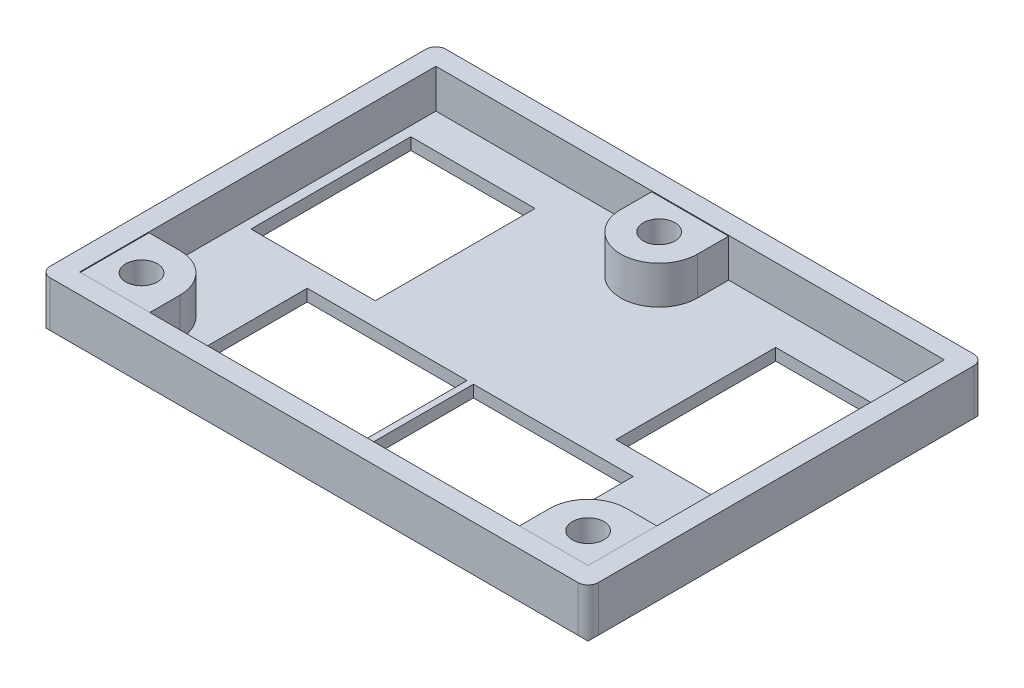
SolidWorks part; units mm, degrees
ref_plane "Front Plane" through (0, 0, 0) normal (0, 0, 1) x (1, 0, 0)
ref_plane "Top Plane" through (0, 0, 0) normal (0, 1, 0) x (1, 0, 0)
ref_plane "Right Plane" through (0, 0, 0) normal (1, 0, 0) x (0, 0, -1)
sketch "Sketch1" plane through (0, 0, 0) normal (0, 1, 0) x (1, 0, 0)
  line L0 (-41.1458, 0) -> (37.3326, 0) construction
  line L1 (-27, -19.5) -> (27, -19.5)
  line L2 (-27, -19.5) -> (-27, 19.5)
  line L3 (-27, 19.5) -> (27, 19.5)
  line L4 (27, -19.5) -> (27, 19.5)
  line L5 (-27, -19.5) -> (27, 19.5) construction
  line L6 (-27, 19.5) -> (27, -19.5) construction
  line L7 (0, 33.589) -> (0, -25.3286) construction
  line L11 (-27, -5) -> (-27, 5)
  point P0 (0, 0)
  point P8 (-32, 0)
  dimension "D1" = 54
  dimension "D2" = 39
extrude "Boss-Extrude1" add sketch "Sketch1" along normal blind 5
sketch "Sketch2" plane through (0, 5, 0) normal (0, 1, 0) x (1, 0, 0)
  line L0 (0, 27.4) -> (0, -30.8783) construction
  line L1 (-42.9811, 0) -> (41.0645, 0) construction
  line L3 (-25.05, -17.55) -> (25.05, -17.55)
  line L4 (-25.05, -17.55) -> (-25.05, 17.55)
  line L5 (-25.05, 17.55) -> (25.05, 17.55)
  line L6 (25.05, -17.55) -> (25.05, 17.55)
  line L7 (-25.05, -17.55) -> (25.05, 17.55) construction
  line L8 (-25.05, 17.55) -> (25.05, -17.55) construction
  point P5 (0, 0)
  dimension "D1" = 50.1
  dimension "D2" = 35.1
extrude "Cut-Extrude1" cut sketch "Sketch2" against normal blind 0.0762
sketch "Sketch3" plane through (0, 4.9238, 0) normal (0, 1, 0) x (1, 0, 0)
  line L0 (0, 25.6254) -> (0, -24.9156) construction
  line L1 (-43.478, 0) -> (41.2775, 0) construction
  line L2 (-5.4043, 14.5) -> (7.1001, 14.5) construction
  line L3 (-3.79, 14.5) -> (-3.79, 17.55)
  line L4 (25.05, 17.55) -> (-25.05, 17.55) construction
  line L5 (3.79, 14.5) -> (3.79, 17.55)
  line L7 (-22, -6.9215) -> (-22, -24.9156) construction
  line L8 (-15.6235, -14.5) -> (-28.7086, -14.5) construction
  line L9 (-18.21, -14.5) -> (-18.21, -17.55)
  line L10 (-25.05, -17.55) -> (25.05, -17.55) construction
  line L11 (-22, -10.71) -> (-25.05, -10.71)
  line L12 (-25.05, 17.55) -> (-25.05, -17.55) construction
  line L13 (-18.21, -17.55) -> (18.21, -17.55)
  line L14 (-25.05, -10.71) -> (-25.05, 17.55)
  line L15 (-25.05, 17.55) -> (-3.79, 17.55)
  line L16 (18.21, -14.5) -> (18.21, -17.55)
  line L17 (22, -10.71) -> (25.05, -10.71)
  line L18 (25.05, -10.71) -> (25.05, 17.55)
  line L19 (25.05, 17.55) -> (3.79, 17.55)
  arc A0 (-3.79, 14.5) -> (3.79, 14.5) centre (0, 14.5) ccw
  arc A1 (-18.21, -14.5) -> (-22, -10.71) centre (-22, -14.5) ccw
  arc A2 (18.21, -14.5) -> (22, -10.71) centre (22, -14.5) cw
  point P31 (0, -17.55)
  dimension "D1" = 7.58
  dimension "D3" = 7.58
  dimension "D2" = 14.5
  dimension "D4" = 22
  dimension "D5" = 14.5
extrude "Cut-Extrude2" cut sketch "Sketch3" against normal blind 3.75
sketch "Sketch4" plane through (0, 4.9238, 0) normal (0, 1, 0) x (1, 0, 0)
  line L0 (0, 26.0262) -> (0, -25.2956) construction
  line L1 (-42.2713, 0) -> (43.691, 0) construction
  circle A0 centre (0, 14.5) radius 1.56
  circle A1 centre (-22, -14.5) radius 1.56
  circle A2 centre (22, -14.5) radius 1.56
  dimension "D1" = 3.12
  dimension "D2" = 14.5
  dimension "D3" = 22
  dimension "D4" = 14.5
extrude "Cut-Extrude3" cut sketch "Sketch4" against normal through all
sketch "Sketch6" plane through (0, 1.1738, 0) normal (0, 1, 0) x (1, 0, 0)
  line L0 (25.05, -17.55) -> (25.05, 17.55) construction
  line L1 (24.1, 14.13) -> (11.85, 14.13)
  line L2 (24.1, 14.13) -> (24.1, -1.62)
  line L3 (24.1, -1.62) -> (11.85, -1.62)
  line L4 (11.85, 14.13) -> (11.85, -1.62)
  line L5 (25.05, 17.55) -> (-25.05, 17.55) construction
  line L6 (-18.21, -17.55) -> (18.21, -17.55) construction
  line L7 (15.85, -3.9) -> (0.1, -3.9)
  line L8 (15.85, -3.9) -> (15.85, -16.4)
  line L9 (15.85, -16.4) -> (0.1, -16.4)
  line L10 (0.1, -3.9) -> (0.1, -16.4)
  line L11 (25.05, -17.55) -> (25.05, -10.71) construction
  line L12 (0, 23.4777) -> (0, -37.1578) construction
  line L13 (-11.85, 14.13) -> (-11.85, -1.62)
  line L14 (-24.1, -1.62) -> (-11.85, -1.62)
  line L15 (-24.1, 14.13) -> (-24.1, -1.62)
  line L16 (-24.1, 14.13) -> (-11.85, 14.13)
  line L18 (-0.525, -3.9) -> (-16.275, -3.9)
  line L19 (-0.525, -3.9) -> (-0.525, -16.4)
  line L20 (-0.525, -16.4) -> (-16.275, -16.4)
  line L21 (-16.275, -3.9) -> (-16.275, -16.4)
  dimension "D1" = 0.95
  dimension "D2" = 12.25
  dimension "D3" = 15.75
  dimension "D4" = 3.42
  dimension "D5" = 12.5
  dimension "D6" = 15.75
  dimension "D7" = 1.15
  dimension "D8" = 9.2
  dimension "D9" = 0.625
  dimension "D10" = 12.5
  dimension "D11" = 15.75
extrude "Cut-Extrude5" cut sketch "Sketch6" against normal through all
chamfer "Chamfer1" distance 0.5 angle 45 4 edges at (27, 0, 0) (0, 0, 19.5) (-27, 0, 0) (0, 0, -19.5)
fillet "Fillet1" radius 1 4 edges at (-27, 2.75, 19.5) (27, 2.75, 19.5) (-27, 2.75, -19.5) (27, 2.75, -19.5)
